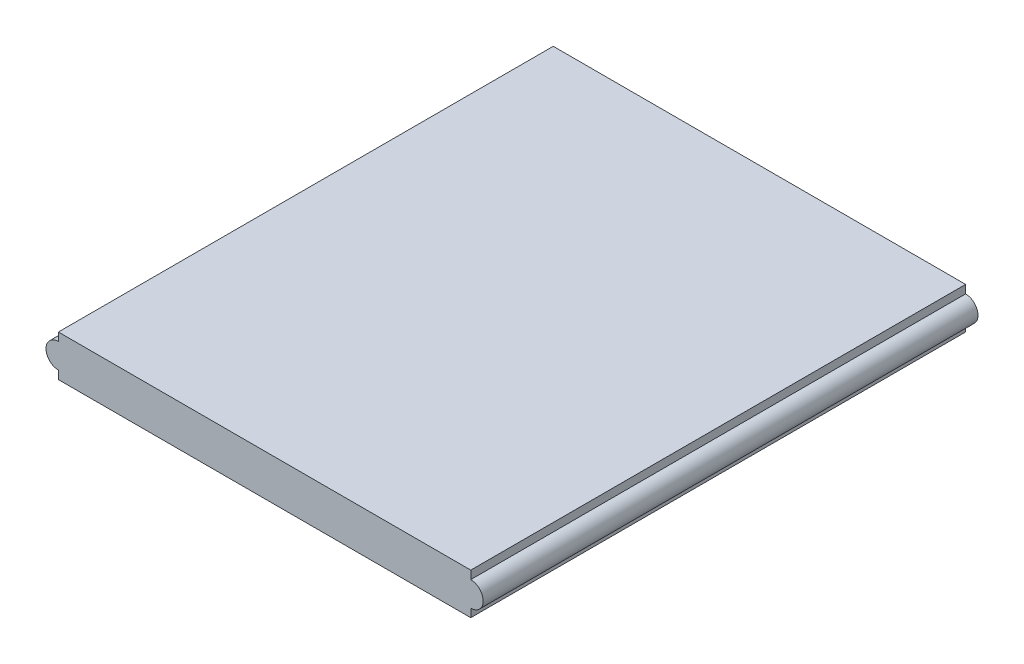
SolidWorks part; units mm, degrees
ref_plane "Alzado" through (0, 0, 0) normal (0, 0, 1) x (1, 0, 0)
ref_plane "Planta" through (0, 0, 0) normal (0, 1, 0) x (1, 0, 0)
ref_plane "Vista lateral" through (0, 0, 0) normal (1, 0, 0) x (0, 0, -1)
sketch "Croquis1" plane through (0, 0, 0) normal (0, 0, 1) x (1, 0, 0)
  line L0 (-71.5081, 44.823) -> (-71.5081, 45.823)
  line L1 (-71.5081, 40.823) -> (-21.5081, 40.823)
  line L2 (-71.5081, 40.823) -> (-71.5081, 41.823)
  line L3 (-71.5081, 45.823) -> (-21.5081, 45.823)
  line L4 (-21.5081, 40.823) -> (-21.5081, 41.823)
  line L5 (-21.5081, 44.823) -> (-21.5081, 45.823)
  arc A0 (-71.5081, 44.823) -> (-71.5081, 41.823) centre (-71.5081, 43.323) ccw
  arc A1 (-21.5081, 41.823) -> (-21.5081, 44.823) centre (-21.5081, 43.323) ccw
  dimension "D1" = 3
  dimension "D2" = 50
  dimension "D3" = 5
extrude "Saliente-Extruir1" add sketch "Croquis1" along normal blind 60
sketch "Croquis3" plane through (0, 0, 0) normal (0, 0, -1) x (-1, 0, 0)
  line L1 (36.5081, 40.823) -> (56.5081, 40.823)
  line L2 (36.5081, 40.823) -> (36.5081, 41.323)
  line L3 (38.5081, 43.323) -> (54.5081, 43.323)
  line L4 (56.5081, 40.823) -> (56.5081, 41.323)
  line L6 (71.5081, 40.823) -> (71.5081, 41.823)
  line L7 (71.5081, 44.823) -> (71.5081, 45.823)
  line L8 (71.5081, 45.823) -> (21.5081, 45.823)
  line L9 (21.5081, 45.823) -> (21.5081, 44.823)
  line L10 (21.5081, 41.823) -> (21.5081, 40.823)
  line L11 (21.5081, 40.823) -> (71.5081, 40.823)
  line L12 (71.5081, 40.823) -> (71.5081, 41.823)
  line L13 (71.5081, 44.823) -> (71.5081, 45.823)
  line L14 (71.5081, 45.823) -> (21.5081, 45.823)
  line L15 (21.5081, 45.823) -> (21.5081, 44.823)
  line L16 (21.5081, 41.823) -> (21.5081, 40.823)
  line L17 (21.5081, 40.823) -> (71.5081, 40.823)
  arc A0 (54.5081, 43.323) -> (56.5081, 41.323) centre (54.5081, 41.323) cw
  arc A1 (36.5081, 41.323) -> (38.5081, 43.323) centre (38.5081, 41.323) cw
  arc A2 (71.5081, 41.823) -> (71.5081, 44.823) centre (71.5081, 43.323) ccw
  arc A3 (21.5081, 44.823) -> (21.5081, 41.823) centre (21.5081, 43.323) ccw
  arc A4 (71.5081, 41.823) -> (71.5081, 44.823) centre (71.5081, 43.323) ccw
  arc A5 (21.5081, 44.823) -> (21.5081, 41.823) centre (21.5081, 43.323) ccw
  point P12 (46.5081, 43.323)
  point P14 (46.5081, 45.823)
  point P18 (56.5081, 43.323)
  point P21 (36.5081, 43.323)
  line M18 (21.5081, 40.823) -> (71.5081, 40.823)
  dimension "D4" = 2
  dimension "D2" = 20
  dimension "D3" = 2.5
  dimension "D1" = 0
extrude "Cortar-Extruir1" cut sketch "Croquis3" along direction (0, 0, 1) on the side against the normal blind 10 contours A1 L2 L4 A0 L3 M18
